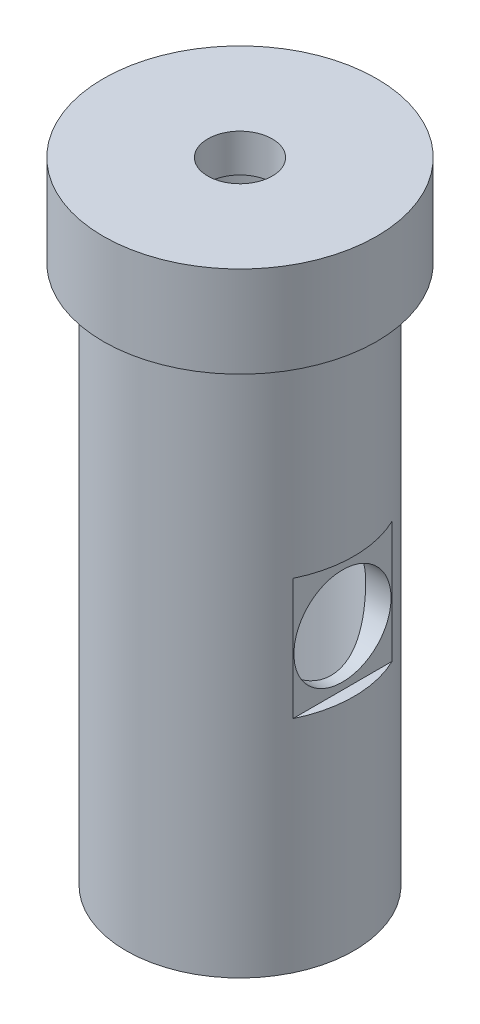
SolidWorks part; units mm, degrees
material "6061-T6 (SS)"
ref_plane "Piano frontale" through (0, 0, 0) normal (0, 0, 1) x (1, 0, 0)
ref_plane "Piano superiore" through (0, 0, 0) normal (0, 1, 0) x (1, 0, 0)
ref_plane "Piano destro" through (0, 0, 0) normal (1, 0, 0) x (0, 0, -1)
sketch "Schizzo1" plane through (0, 0, 0) normal (0, 0, 1) x (1, 0, 0)
  line L0 (0, 0) -> (0, 31.0712) construction
  line L1 (-12, 0) -> (-15, 0)
  line L2 (-15, 0) -> (-15, 71)
  line L3 (-15, 71) -> (-18, 71)
  line L4 (-18, 71) -> (-18, 83)
  line L5 (-18, 83) -> (-4.25, 83)
  line L6 (-4.25, 83) -> (-4.25, 78)
  line L7 (-4.25, 78) -> (-12, 78)
  line L8 (-12, 78) -> (-12, 0)
  dimension "D1" = 24
  dimension "D2" = 30
  dimension "D3" = 36
  dimension "D4" = 5
  dimension "D5" = 78
  dimension "D6" = 12
  dimension "D7" = 8.5
revolve "Rivoluzione1" add sketch "Schizzo1" angle 360 about L0
sketch "Schizzo2" plane through (0, 0, 0) normal (1, 0, 0) x (0, 0, -1)
  line L1 (8, 45) -> (-8, 45)
  line L2 (8, 45) -> (8, 29)
  line L3 (8, 29) -> (-8, 29)
  line L4 (-8, 45) -> (-8, 29)
  line L5 (8, 45) -> (-8, 29) construction
  line L6 (8, 29) -> (-8, 45) construction
  point P0 (0, 37)
  point P5 (0, 0)
  dimension "D1" = 16
  dimension "D2" = 37
extrude "Taglio-Estrusione1" cut sketch "Schizzo2" against normal blind 1.5 from offset 15
hole_wizard "Foro Ø12.8 (12.8)-1" positions "Schizzo3" profile "Schizzo4" hole size "Ø12.8" standard "ISO"
sketch "Schizzo3" plane through (13.5, 0, 0) normal (1, 0, 0) x (0, 0, -1)
  point P0 (0, 36.3049)
  point P1 (0, 34.4969)
  point P2 (0, 35.4798)
  point P3 (0, 37.6913)
  point P4 (0, 36.5856)
  point P5 (0, 36.3049)
sketch "Schizzo4" plane through (13.5, 36.3049, 0) normal (0, 1, 0) x (0, 0, -1)
  line L0 (0, 0) -> (0, 19)
  line L1 (0, 19) -> (6.4, 15.1545)
  line L2 (6.4, 15.1545) -> (6.4, 0)
  line L5 (6.4, 0) -> (0, 0)
  line L10 (0, 19) -> (-6.4, 15.1545) construction
  line L11 (0, -6.35) -> (0, 107.95) construction
  dimension "Hole Dia." = 12.8
  dimension "Hole Depth" = 19
  dimension "Drill Angle" = 118
